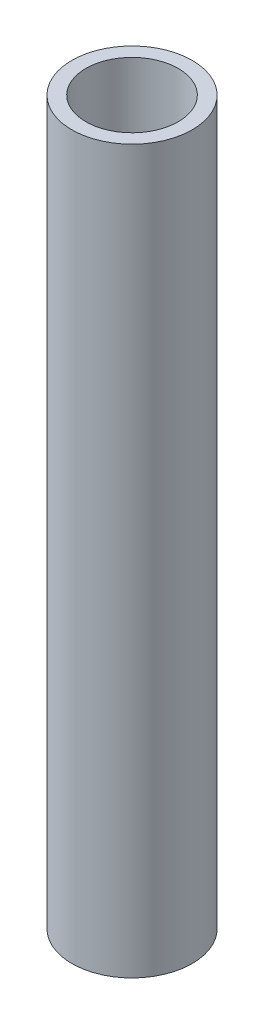
SolidWorks part; units mm, degrees
material "AISI 4130 Steel, normalized at 870C"
ref_plane "X-Y Datum" through (0, 0, 0) normal (0, 0, 1) x (1, 0, 0)
ref_plane "X-Z Datum" through (0, 0, 0) normal (0, 1, 0) x (1, 0, 0)
ref_plane "Y-Z Datum" through (0, 0, 0) normal (1, 0, 0) x (0, 0, -1)
sketch "Sketch2" plane through (0, 0, 0) normal (0, 1, 0) x (1, 0, 0)
  circle A0 centre (0, 0) radius 6.35
  circle A1 centre (0, 0) radius 4.8768
  dimension "D1" = 12.7
  dimension "D2" = 1.4732
extrude "Boss-Extrude1" add sketch "Sketch2" along normal mid plane 76.2
equation "\"Droplink rod OD\" = 0.5in"
equation "\"Droplink rod wall thickness\"=0.058"
equation "\"Droplink rod length\"= 3in"
equation "\"D1@Sketch2\"=\"Droplink rod OD\""
equation "\"D2@Sketch2\"=\"Droplink rod wall thickness\""
equation "\"D1@Boss-Extrude1\"=\"Droplink rod length\""
